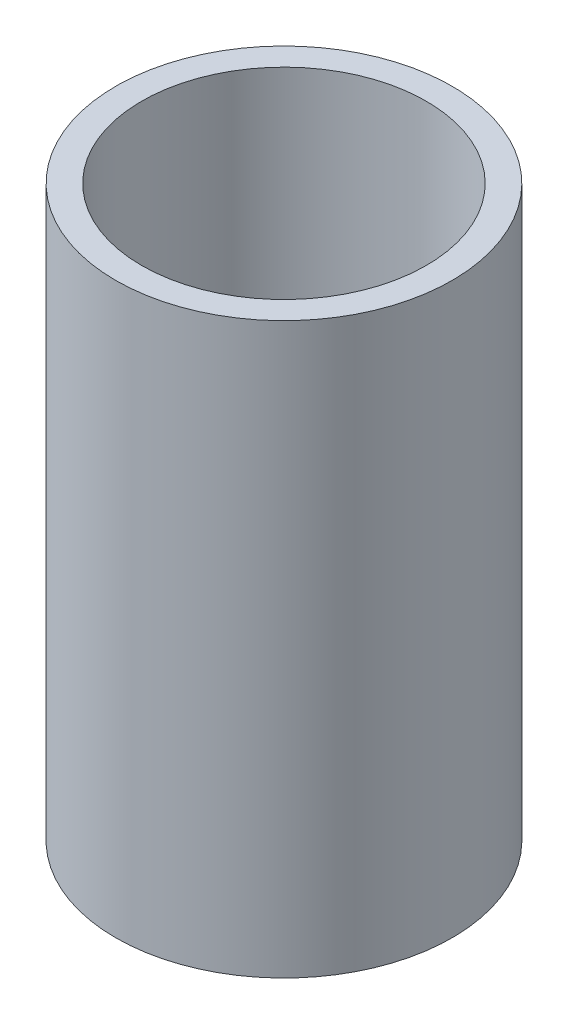
SolidWorks part; units mm, degrees
ref_plane "Front Plane" through (0, 0, 0) normal (0, 0, 1) x (1, 0, 0)
ref_plane "Top Plane" through (0, 0, 0) normal (0, 1, 0) x (1, 0, 0)
ref_plane "Right Plane" through (0, 0, 0) normal (1, 0, 0) x (0, 0, -1)
sketch "Sketch1" plane through (0, 0, 0) normal (0, 1, 0) x (1, 0, 0)
  circle A0 centre (0, 0) radius 2.75
  circle A1 centre (0, 0) radius 3.25
  dimension "D1" = 5.5
  dimension "D2" = 6.5
extrude "Boss-Extrude1" add sketch "Sketch1" along normal blind 11
